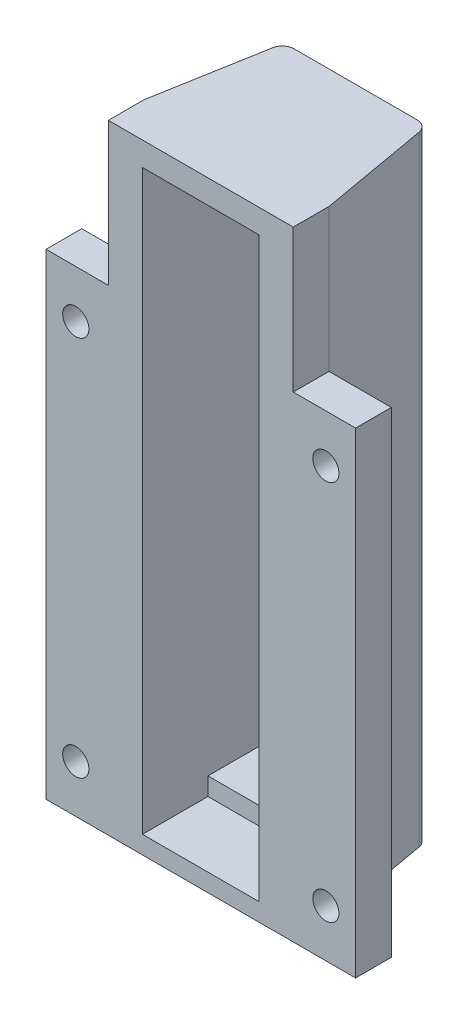
SolidWorks part; units mm, degrees
ref_plane "前视基准面" through (0, 0, 0) normal (0, 0, 1) x (1, 0, 0)
ref_plane "上视基准面" through (0, 0, 0) normal (0, 1, 0) x (1, 0, 0)
ref_plane "右视基准面" through (0, 0, 0) normal (1, 0, 0) x (0, 0, -1)
sketch "草图1" plane through (0, 0, 0) normal (0, 1, 0) x (1, 0, 0)
  line L0 (0, 0) -> (0, 11.5) construction
  line L1 (-13, -1.5) -> (13, -1.5)
  line L2 (-13, -1.5) -> (-13, 1.5)
  line L3 (-13, 1.5) -> (13, 1.5)
  line L4 (13, -1.5) -> (13, 1.5)
  line L5 (-13, -1.5) -> (13, 1.5) construction
  line L6 (-13, 1.5) -> (13, -1.5) construction
  line L7 (-6, 11.5) -> (6, 11.5)
  line L8 (6, 11.5) -> (8.2923, -1.5)
  line L9 (-6, 11.5) -> (-8.2923, -1.5)
  point P0 (0, 0)
  dimension "D1" = 26
  dimension "D2" = 3
  dimension "D3" = 80
  dimension "D4" = 12
  dimension "D5" = 13
extrude "凸台-拉伸1" add sketch "草图1" along normal blind 40 contours L7 L9 L3 L8 | L3 L9 L1 L8 | L9 L3 L2 L1 | L3 L8 L1 L4
sketch "草图2" plane through (0, 40, 0) normal (0, 1, 0) x (1, 0, 0)
  line L0 (6, 11.5) -> (7.7633, 1.5) construction
  line L1 (-6, 11.5) -> (6, 11.5) construction
  line L2 (-6, 11.5) -> (-7.7633, 1.5) construction
  line L3 (6, 11.5) -> (7.7633, 1.5)
  line L4 (-6, 11.5) -> (6, 11.5)
  line L5 (-6, 11.5) -> (-7.7633, 1.5)
  line L6 (-7.7633, 1.5) -> (-7.7633, -1.5)
  line L7 (-13, -1.5) -> (13, -1.5) construction
  line L8 (-7.7633, -1.5) -> (7.7633, -1.5)
  line L9 (7.7633, -1.5) -> (7.7633, 1.5)
extrude "凸台-拉伸2" add sketch "草图2" along normal blind 12
sketch "草图3" plane through (0, 0, 1.5) normal (0, 0, 1) x (1, 0, 0)
  line L0 (0, 0) -> (0, 25.75) construction
  line L1 (-7.7633, 52) -> (7.7633, 52) construction
  line L2 (-4.9, 3) -> (4.9, 3)
  line L3 (-4.9, 3) -> (-4.9, 48.5)
  line L4 (-4.9, 48.5) -> (4.9, 48.5)
  line L5 (4.9, 3) -> (4.9, 48.5)
  line L6 (-4.9, 3) -> (4.9, 48.5) construction
  line L7 (-4.9, 48.5) -> (4.9, 3) construction
  dimension "D1" = 9.8
  dimension "D2" = 45.5
  dimension "D3" = 3.5
extrude "切除-拉伸1" cut sketch "草图3" against normal offset from surface (10 mm away) 3 up to face at (0, 26, -11.5)
sketch "草图4" plane through (0, 0, 1.5) normal (0, 0, 1) x (1, 0, 0)
  line L0 (0, 48.5) -> (0, 3) construction
  line L2 (-4.9, 1.5) -> (4.9, 1.5)
  line L3 (-4.9, 1.5) -> (-4.9, 50)
  line L4 (4.9, 3) -> (4.9, 48.5)
  line L5 (4.9, 48.5) -> (-4.9, 48.5)
  line L6 (-4.9, 48.5) -> (-4.9, 3)
  line L7 (-4.9, 3) -> (4.9, 3)
  line L8 (4.9, 3) -> (4.9, 48.5) construction
  line L9 (4.9, 48.5) -> (-4.9, 48.5) construction
  line L10 (-4.9, 48.5) -> (-4.9, 3) construction
  line L11 (-4.9, 3) -> (4.9, 3) construction
  line L12 (-4.9, 50) -> (4.9, 50)
  line L13 (4.9, 1.5) -> (4.9, 50)
  line L14 (-4.9, 1.5) -> (4.9, 50) construction
  line L15 (-4.9, 50) -> (4.9, 1.5) construction
  point P6 (0, 25.75)
  dimension "D2" = 1.5
  dimension "D1" = 0
extrude "切除-拉伸2" cut sketch "草图4" against normal offset from surface (5.5 mm away) 4.5 up to face at (0, 25.75, -8.5)
sketch "草图5" plane through (0, 0, 1.5) normal (0, 0, 1) x (1, 0, 0)
  line L0 (-13, 20) -> (19.9241, 20) construction
  line L1 (-13, 40) -> (-13, 0) construction
  line L2 (0, 0) -> (0, 29.4986) construction
  line L3 (-13, 40) -> (-7.7633, 40) construction
  circle A0 centre (-10.5, 36) radius 1.1
  circle A1 centre (-10.5, 4) radius 1.1
  circle A2 centre (10.5, 4) radius 1.1
  circle A3 centre (10.5, 36) radius 1.1
  dimension "D1" = 2.2
  dimension "D2" = 2.5
  dimension "D3" = 4
extrude "切除-拉伸3" cut sketch "草图5" against normal through all
sketch "草图6" plane through (0, 0, -8.5) normal (0, 0, 1) x (1, 0, 0)
  line L0 (0, 48.5) -> (0, 3) construction
  line L2 (-1.75, 8.25) -> (1.75, 8.25)
  line L3 (-1.75, 8.25) -> (-1.75, 43.25)
  line L4 (4.9, 3) -> (4.9, 48.5)
  line L5 (4.9, 48.5) -> (-4.9, 48.5)
  line L6 (-4.9, 48.5) -> (-4.9, 3)
  line L7 (-4.9, 3) -> (4.9, 3)
  line L8 (4.9, 3) -> (4.9, 48.5) construction
  line L9 (4.9, 48.5) -> (-4.9, 48.5) construction
  line L10 (-4.9, 48.5) -> (-4.9, 3) construction
  line L11 (-4.9, 3) -> (4.9, 3) construction
  line L12 (-1.75, 43.25) -> (1.75, 43.25)
  line L13 (1.75, 8.25) -> (1.75, 43.25)
  line L14 (-1.75, 8.25) -> (1.75, 43.25) construction
  line L15 (-1.75, 43.25) -> (1.75, 8.25) construction
  point P6 (0, 25.75)
  dimension "D2" = 3.5
  dimension "D3" = 35
  dimension "D1" = 0
extrude "切除-拉伸4" cut sketch "草图6" against normal through all
sketch "草图7" plane through (0, 0, -8.5) normal (0, 0, 1) x (1, 0, 0)
  line L0 (0, 8.25) -> (0, 46.25) construction
  line L1 (-1.75, 8.25) -> (1.75, 8.25) construction
  line L2 (1.75, 25.75) -> (15.714, 25.75) construction
  line L3 (1.75, 8.25) -> (1.75, 43.25) construction
  circle A0 centre (0, 46.25) radius 1.1
  circle A1 centre (0, 5.25) radius 1.1
  dimension "D1" = 2.2
  dimension "D2" = 41
extrude "切除-拉伸5" cut sketch "草图7" against normal through all
sketch "草图8" plane through (0, 0, -11.5) normal (0, 0, -1) x (-1, 0, 0)
  circle A0 centre (0, 46.25) radius 1.1 construction
  circle A1 centre (0, 46.25) radius 1.1 construction
  circle A2 centre (0, 5.25) radius 1.1 construction
  circle A3 centre (0, 5.25) radius 1.1 construction
  circle A4 centre (0, 46.25) radius 1.95
  circle A5 centre (0, 5.25) radius 1.95
  dimension "D1" = 3.9
extrude "切除-拉伸6" cut sketch "草图8" against normal blind 1.2
chamfer "倒角1" [suppressed] distance 5.24 angle 45
fillet "圆角2" radius 1 2 edges at (6, 26, -11.5) (-6, 26, -11.5)
